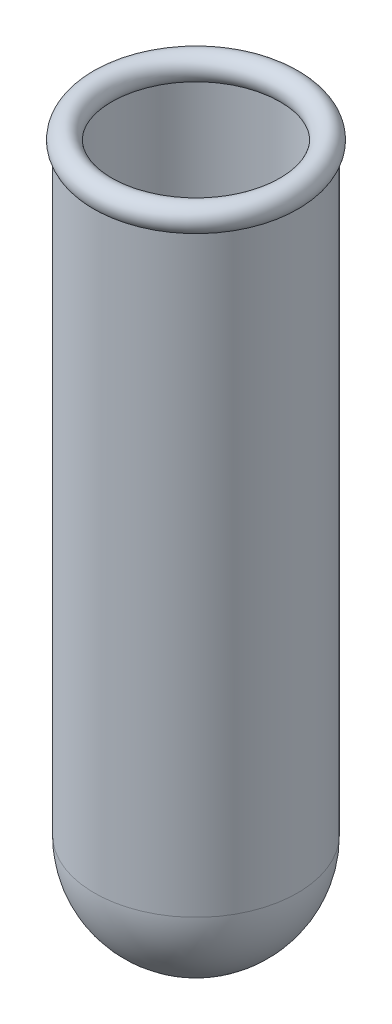
SolidWorks part; units mm, degrees
ref_plane "Front Plane" through (0, 0, 0) normal (0, 0, 1) x (1, 0, 0)
ref_plane "Top Plane" through (0, 0, 0) normal (0, 1, 0) x (1, 0, 0)
ref_plane "Right Plane" through (0, 0, 0) normal (1, 0, 0) x (0, 0, -1)
sketch "Sketch1" plane through (0, 0, 0) normal (0, 0, 1) x (1, 0, 0)
  line L0 (6, 0) -> (6, 35)
  line L2 (-5, 0) -> (-5, 35)
  line L3 (-5, 35) -> (5, 35)
  line L4 (5, 0) -> (5, 35)
  line L5 (-6, 36) -> (4.8933, 36)
  line L6 (-6, 0) -> (-6, 36)
  line L7 (0, 0) -> (0, 35) construction
  line L8 (-6, 36) -> (6, 36) construction
  line L9 (6, 0) -> (6, 36) construction
  line L10 (0, -5) -> (0, -6)
  line L13 (5, -3.3166) -> (5, -6)
  line L14 (5, -6) -> (6, -6)
  line L15 (6, 0) -> (6, -6)
  arc A0 (-5, 0) -> (5, 0) centre (0, 0) ccw
  arc A1 (-6, 0) -> (6, 0) centre (0, 0) ccw
  arc A5 (6, 35) -> (5, 35) centre (5.5, 35.559) ccw
  point P13 (5.5, 34.9258)
  dimension "D1" = 12
  dimension "D4" = 1.5
  dimension "D2" = 42
  dimension "D3" = 1
revolve "Revolve1" add sketch "Sketch1" angle 360 about L7
